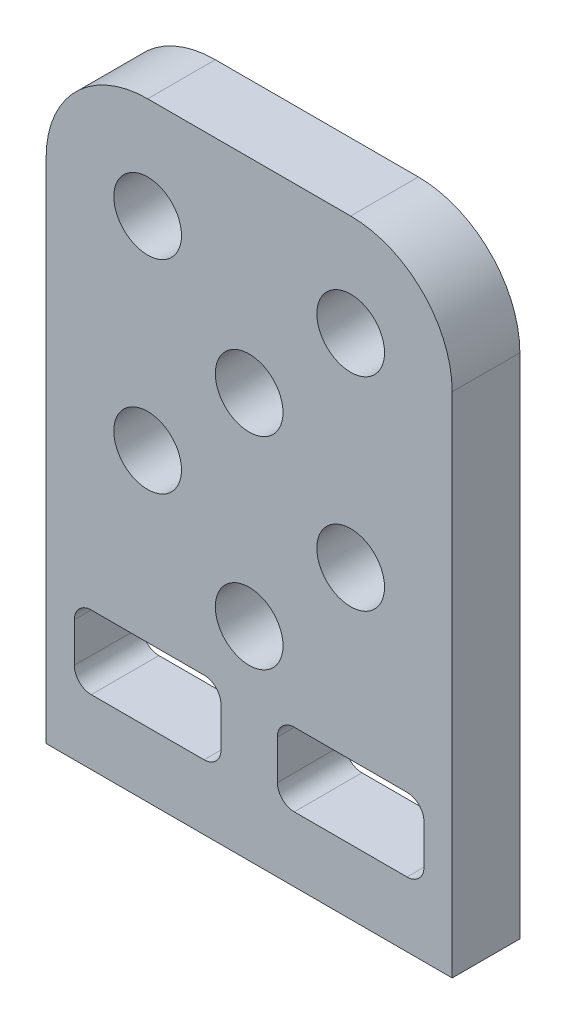
SolidWorks part; units mm, degrees
ref_plane "Alzado" through (0, 0, 0) normal (0, 0, 1) x (1, 0, 0)
ref_plane "Planta" through (0, 0, 0) normal (0, 1, 0) x (1, 0, 0)
ref_plane "Vista lateral" through (0, 0, 0) normal (1, 0, 0) x (0, 0, -1)
sketch "Model" plane through (0, 0, 0) normal (0, 0, 1) x (1, 0, 0)
  line L0 (174.2271, 190.6759) -> (192.2271, 190.6759)
  line L1 (174.2271, 213.1787) -> (174.2271, 190.6759)
  line L2 (187.7271, 217.6787) -> (178.7271, 217.6787)
  line L3 (192.2271, 190.6759) -> (192.2271, 213.1787)
  line L4 (190.2271, 193.5537) -> (185.2271, 193.5537)
  line L5 (184.4771, 194.3037) -> (184.4771, 196.0537)
  line L6 (185.2271, 196.8037) -> (190.2271, 196.8037)
  line L7 (190.9771, 196.0537) -> (190.9771, 194.3037)
  line L8 (181.2271, 193.5537) -> (176.2271, 193.5537)
  line L9 (175.4771, 194.3037) -> (175.4771, 196.0537)
  line L10 (176.2271, 196.8037) -> (181.2271, 196.8037)
  line L11 (181.9771, 196.0537) -> (181.9771, 194.3037)
  circle A0 centre (183.2271, 199.6787) radius 1.5
  circle A1 centre (183.2271, 208.6321) radius 1.5
  circle A2 centre (187.7271, 204.1787) radius 1.5
  circle A3 centre (178.7271, 204.1787) radius 1.5
  circle A4 centre (187.7271, 213.1787) radius 1.5
  arc A5 (178.7271, 217.6787) -> (174.2271, 213.1787) centre (178.7271, 213.1787) ccw
  arc A6 (192.2271, 213.1787) -> (187.7271, 217.6787) centre (187.7271, 213.1787) ccw
  circle A7 centre (178.7271, 213.1787) radius 1.5
  arc A8 (184.4771, 194.3037) -> (185.2271, 193.5537) centre (185.2271, 194.3037) ccw
  arc A9 (185.2271, 196.8037) -> (184.4771, 196.0537) centre (185.2271, 196.0537) ccw
  arc A10 (190.9771, 196.0537) -> (190.2271, 196.8037) centre (190.2271, 196.0537) ccw
  arc A11 (190.2271, 193.5537) -> (190.9771, 194.3037) centre (190.2271, 194.3037) ccw
  arc A13 (175.4771, 194.3037) -> (176.2271, 193.5537) centre (176.2271, 194.3037) ccw
  arc A14 (176.2271, 196.8037) -> (175.4771, 196.0537) centre (176.2271, 196.0537) ccw
  arc A15 (181.9771, 196.0537) -> (181.2271, 196.8037) centre (181.2271, 196.0537) ccw
  arc A16 (181.2271, 193.5537) -> (181.9771, 194.3037) centre (181.2271, 194.3037) ccw
extrude "Saliente-Extruir1" add sketch "Model" along normal blind 3
